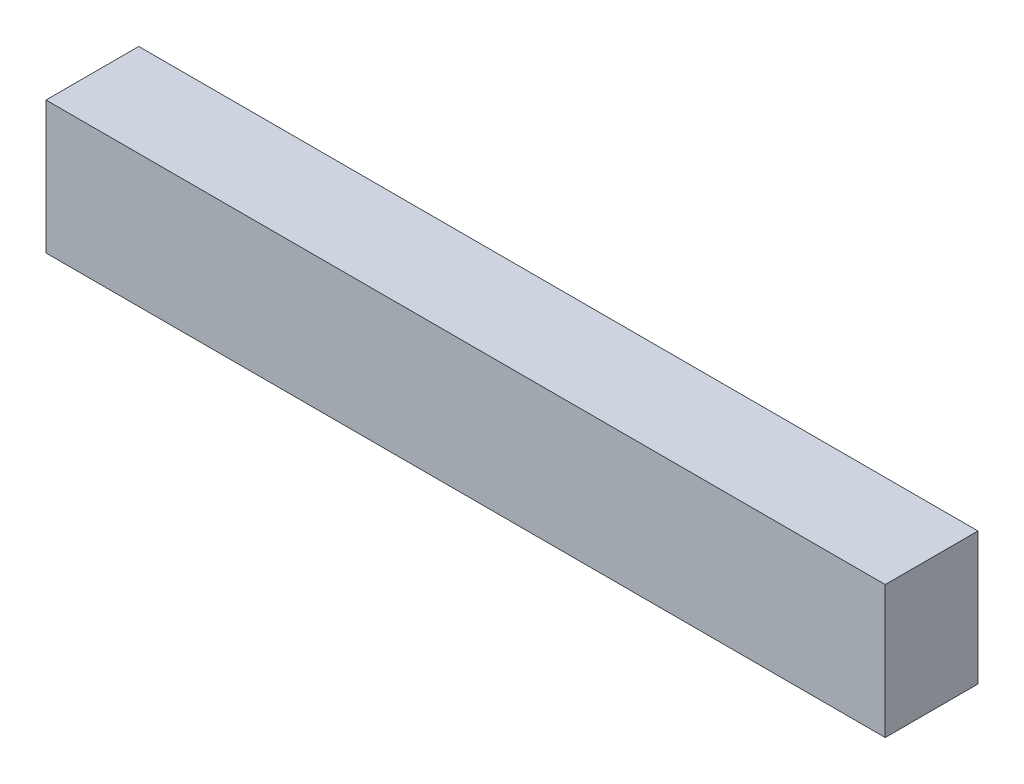
SolidWorks part; units mm, degrees
ref_plane "Front Plane" through (0, 0, 0) normal (0, 0, 1) x (1, 0, 0)
ref_plane "Top Plane" through (0, 0, 0) normal (0, 1, 0) x (1, 0, 0)
ref_plane "Right Plane" through (0, 0, 0) normal (1, 0, 0) x (0, 0, -1)
sketch "Sketch1" plane through (0, 0, 0) normal (0, 0, 1) x (1, 0, 0)
  line L1 (-34.4608, 13.5095) -> (13.7992, 13.5095)
  line L2 (-34.4608, 13.5095) -> (-34.4608, 5.8895)
  line L3 (-34.4608, 5.8895) -> (13.7992, 5.8895)
  line L4 (13.7992, 13.5095) -> (13.7992, 5.8895)
  dimension "D1" = 48.26
  dimension "D2" = 7.62
extrude "Boss-Extrude1" add sketch "Sketch1" along normal blind 5.334
equation "\"MDF\" = .21"
equation "\"Foamcore\"= .13in"
equation "\"Gmaterial\"= \"MDF\""
equation "\"D1@Boss-Extrude1\"=\"MDF\""
